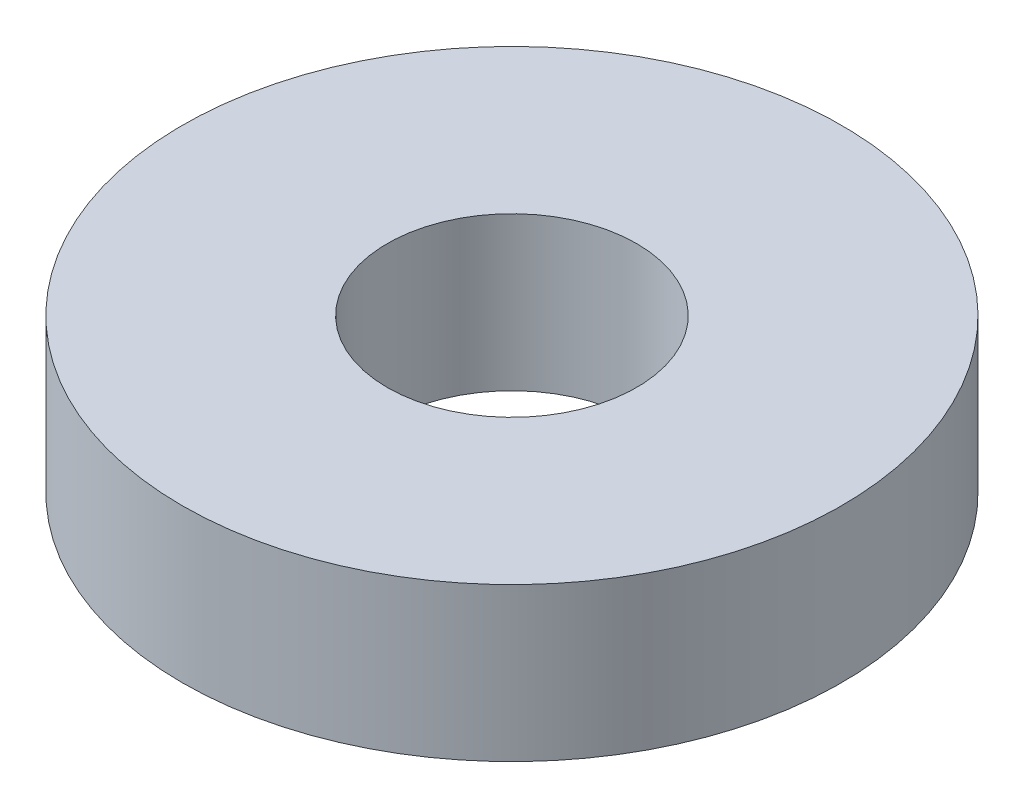
SolidWorks part; units mm, degrees
ref_plane "前视基准面" through (0, 0, 0) normal (0, 0, 1) x (1, 0, 0)
ref_plane "上视基准面" through (0, 0, 0) normal (0, 1, 0) x (1, 0, 0)
ref_plane "右视基准面" through (0, 0, 0) normal (1, 0, 0) x (0, 0, -1)
other "Configuration Table"
sketch "草图1" plane through (0, 0, 0) normal (0, 1, 0) x (1, 0, 0)
  circle A0 centre (0, 0) radius 32.2427
  circle A1 centre (0, 0) radius 12.2
  dimension "D1" = 24.4
extrude "凸台-拉伸1" add sketch "草图1" along normal blind 15
